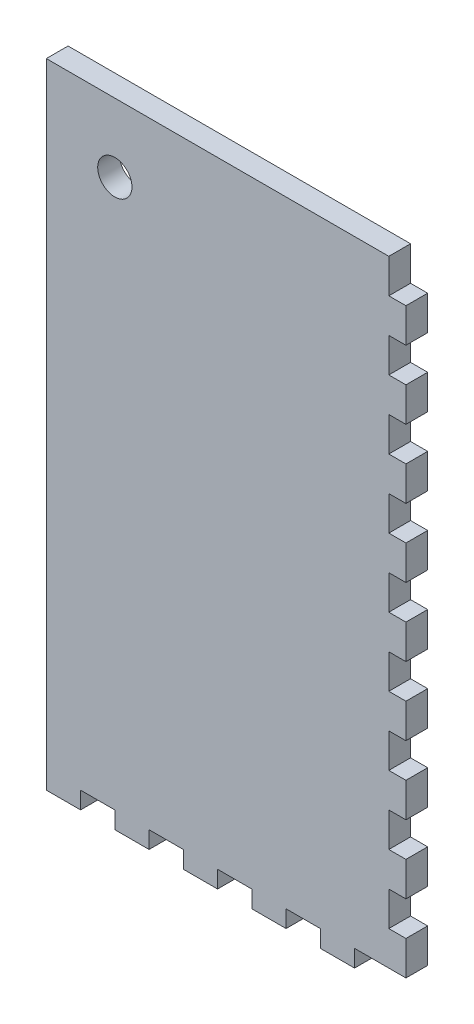
SolidWorks part; units mm, degrees
ref_plane "Front Plane" through (0, 0, 0) normal (0, 0, 1) x (1, 0, 0)
ref_plane "Top Plane" through (0, 0, 0) normal (0, 1, 0) x (1, 0, 0)
ref_plane "Right Plane" through (0, 0, 0) normal (1, 0, 0) x (0, 0, -1)
sketch "Sketch1" plane through (0, 0, 0) normal (0, 0, 1) x (1, 0, 0)
  line L1 (0, 0) -> (50, 0)
  line L2 (0, 0) -> (0, 90)
  line L3 (0, 90) -> (50, 90)
  line L4 (50, 0) -> (50, 90)
  dimension "D1" = 90
  dimension "D2" = 50
extrude "Boss-Extrude2" add sketch "Sketch1" along normal blind 3.175
sketch "Sketch2" plane through (50, 0, 0) normal (1, 0, 0) x (0, 0, -1)
  line L0 (0, 0) -> (0, 90) construction
  line L1 (-3.175, 0) -> (0, 0)
  line L2 (-3.175, 0) -> (-3.175, 5)
  line L3 (-3.175, 5) -> (0, 5)
  line L4 (0, 0) -> (0, 5)
  dimension "D1" = 5
extrude "Boss-Extrude3" add sketch "Sketch2" along normal blind 2.5
pattern_linear "LPattern1" count 9 spacing 10 along (0, 1, 0) of "Boss-Extrude3"
sketch "Sketch3" plane through (0, 0, 0) normal (0, -1, 0) x (1, 0, 0)
  line L0 (0, 0) -> (52.5, 0) construction
  line L1 (0, 3.175) -> (5, 3.175)
  line L2 (0, 3.175) -> (0, 0)
  line L3 (0, 0) -> (5, 0)
  line L4 (5, 3.175) -> (5, 0)
  dimension "D1" = 5
extrude "Boss-Extrude4" add sketch "Sketch3" along normal blind 2.5
pattern_linear "LPattern2" count 5 spacing 10 along (1, 0, 0) of "Boss-Extrude4"
sketch "Sketch4" plane through (0, 0, 3.175) normal (0, 0, 1) x (1, 0, 0)
  line L1 (50, 90) -> (0, 90) construction
  line L2 (0, 90) -> (0, -2.5) construction
  circle A0 centre (10, 80) radius 2.5
  dimension "D2" = 10
  dimension "D3" = 5
  dimension "D1" = 10
extrude "Cut-Extrude1" cut sketch "Sketch4" against normal blind 10
